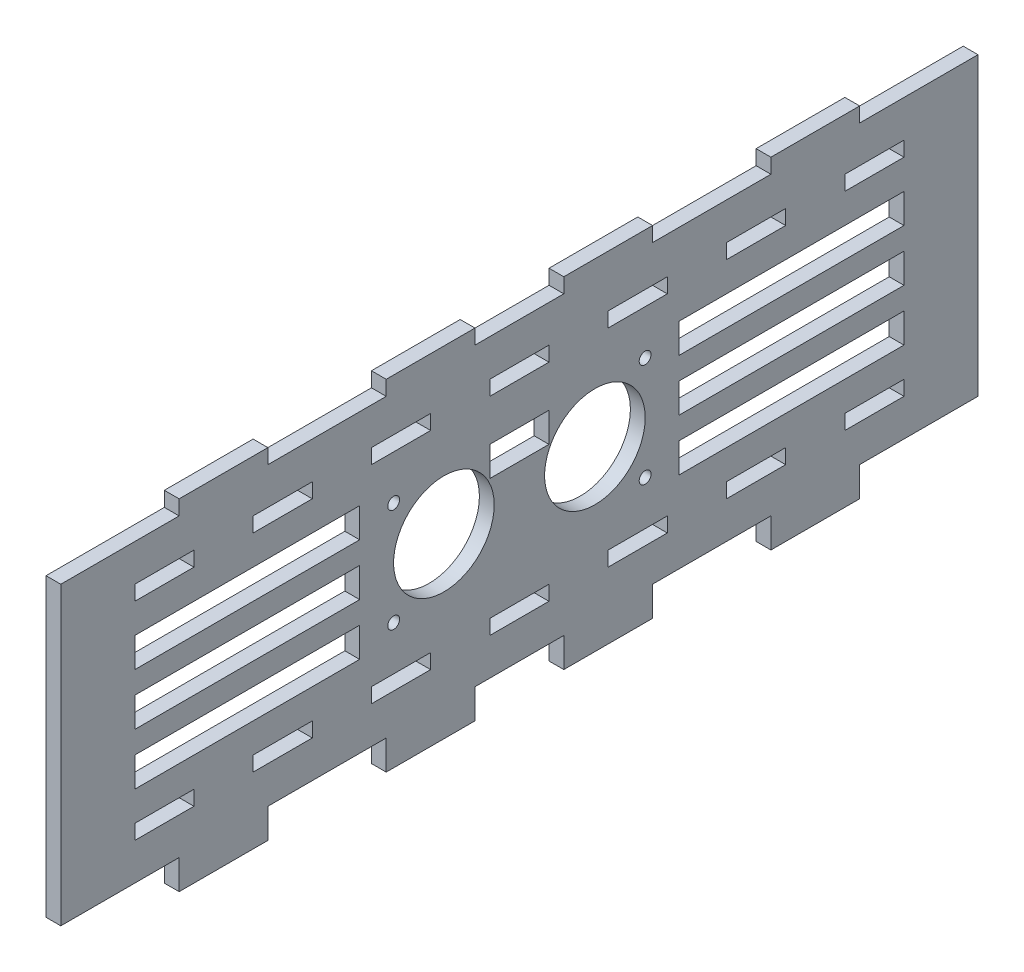
SolidWorks part; units mm, degrees
material "Maple"
ref_plane "Front Plane" through (0, 0, 0) normal (0, 0, 1) x (1, 0, 0)
ref_plane "Top Plane" through (0, 0, 0) normal (0, 1, 0) x (1, 0, 0)
ref_plane "Right Plane" through (0, 0, 0) normal (1, 0, 0) x (0, 0, -1)
sketch "Sketch1" plane through (0, 0, 0) normal (1, 0, 0) x (0, 0, -1)
  line L0 (-77.507, 27.5) -> (77.507, 27.5) construction
  line L1 (-77.507, -25) -> (77.507, -25) construction
  line L2 (-77.507, -25) -> (-77.507, 25) construction
  line L3 (-77.507, 25) -> (77.507, 25) construction
  line L4 (77.507, -25) -> (77.507, 25) construction
  line L5 (-77.507, -25) -> (77.507, 25) construction
  line L6 (-77.507, 25) -> (77.507, -25) construction
  line L7 (-77.507, -30) -> (77.507, -30) construction
  line L8 (-20.5112, 0) -> (21.2154, 0) construction
  line L9 (0, 22.6869) -> (0, -9.8875) construction
  line L10 (-77.507, 25) -> (-77.507, -25)
  line L11 (-77.507, -25) -> (-57.507, -25)
  line L12 (-57.507, -25) -> (-57.507, -30)
  line L13 (-57.507, -30) -> (-42.507, -30)
  line L14 (-42.507, -30) -> (-42.507, -25)
  line L15 (-42.507, -25) -> (-22.507, -25)
  line L16 (-22.507, -25) -> (-22.507, -30)
  line L17 (-22.507, -30) -> (-7.507, -30)
  line L18 (-7.507, -30) -> (-7.507, -25)
  line L19 (-7.507, -25) -> (7.507, -25)
  line L20 (-7.507, 25) -> (7.507, 25)
  line L21 (-7.507, 27.5) -> (-7.507, 25)
  line L22 (-22.507, 27.5) -> (-7.507, 27.5)
  line L23 (-22.507, 25) -> (-22.507, 27.5)
  line L24 (-42.507, 25) -> (-22.507, 25)
  line L25 (-42.507, 27.5) -> (-42.507, 25)
  line L26 (-57.507, 27.5) -> (-42.507, 27.5)
  line L27 (-57.507, 25) -> (-57.507, 27.5)
  line L28 (-77.507, 25) -> (-57.507, 25)
  line L29 (7.507, -30) -> (7.507, -25)
  line L30 (22.507, -30) -> (7.507, -30)
  line L31 (22.507, -25) -> (22.507, -30)
  line L32 (42.507, -25) -> (22.507, -25)
  line L33 (42.507, -30) -> (42.507, -25)
  line L34 (57.507, -30) -> (42.507, -30)
  line L35 (57.507, -25) -> (57.507, -30)
  line L36 (77.507, -25) -> (57.507, -25)
  line L37 (77.507, 25) -> (77.507, -25)
  line L38 (77.507, 25) -> (57.507, 25)
  line L39 (57.507, 25) -> (57.507, 27.5)
  line L40 (57.507, 27.5) -> (42.507, 27.5)
  line L41 (42.507, 27.5) -> (42.507, 25)
  line L42 (42.507, 25) -> (22.507, 25)
  line L43 (22.507, 25) -> (22.507, 27.5)
  line L44 (22.507, 27.5) -> (7.507, 27.5)
  line L45 (7.507, 27.5) -> (7.507, 25)
  line L46 (-5, 16.25) -> (5, 16.25)
  line L51 (-65, -11.25) -> (-65, -6.25)
  line L52 (-27, -11.25) -> (-65, -11.25)
  line L57 (-27, -6.25) -> (-27, -11.25)
  line L58 (-65, -6.25) -> (-27, -6.25)
  line L59 (-5, -18.75) -> (5, -18.75)
  line L60 (-5, -18.75) -> (-5, -16.25)
  line L61 (-5, -16.25) -> (5, -16.25)
  line L62 (5, -18.75) -> (5, -16.25)
  line L63 (-5, -18.75) -> (5, -16.25) construction
  line L64 (-5, -16.25) -> (5, -18.75) construction
  line L65 (5, 18.75) -> (5, 16.25)
  line L66 (-5, 18.75) -> (5, 18.75)
  line L67 (-5, 18.75) -> (-5, 16.25)
  line L68 (-25, -18.75) -> (-25, -16.25)
  line L69 (-25, -18.75) -> (-15, -18.75)
  line L70 (-15, -18.75) -> (-15, -16.25)
  line L71 (-25, -16.25) -> (-15, -16.25)
  line L72 (-25, 16.25) -> (-15, 16.25)
  line L73 (-15, 18.75) -> (-15, 16.25)
  line L74 (-25, 18.75) -> (-15, 18.75)
  line L75 (-25, 18.75) -> (-25, 16.25)
  line L76 (-45, -18.75) -> (-45, -16.25)
  line L77 (-45, -18.75) -> (-35, -18.75)
  line L78 (-35, -18.75) -> (-35, -16.25)
  line L79 (-45, -16.25) -> (-35, -16.25)
  line L80 (-45, 16.25) -> (-35, 16.25)
  line L81 (-35, 18.75) -> (-35, 16.25)
  line L82 (-45, 18.75) -> (-35, 18.75)
  line L83 (-45, 18.75) -> (-45, 16.25)
  line L84 (-65, -18.75) -> (-65, -16.25)
  line L85 (-65, -18.75) -> (-55, -18.75)
  line L86 (-55, -18.75) -> (-55, -16.25)
  line L87 (-65, -16.25) -> (-55, -16.25)
  line L88 (-65, 16.25) -> (-55, 16.25)
  line L89 (-55, 18.75) -> (-55, 16.25)
  line L90 (-65, 18.75) -> (-55, 18.75)
  line L91 (-65, 18.75) -> (-65, 16.25)
  line L92 (15, -18.75) -> (15, -16.25)
  line L93 (15, -18.75) -> (25, -18.75)
  line L94 (25, -18.75) -> (25, -16.25)
  line L95 (15, -16.25) -> (25, -16.25)
  line L96 (15, 16.25) -> (25, 16.25)
  line L97 (25, 18.75) -> (25, 16.25)
  line L98 (15, 18.75) -> (25, 18.75)
  line L99 (15, 18.75) -> (15, 16.25)
  line L100 (35, -18.75) -> (35, -16.25)
  line L101 (35, -18.75) -> (45, -18.75)
  line L102 (45, -18.75) -> (45, -16.25)
  line L103 (35, -16.25) -> (45, -16.25)
  line L104 (35, 16.25) -> (45, 16.25)
  line L105 (45, 18.75) -> (45, 16.25)
  line L106 (35, 18.75) -> (45, 18.75)
  line L107 (35, 18.75) -> (35, 16.25)
  line L108 (55, -18.75) -> (55, -16.25)
  line L109 (55, -18.75) -> (65, -18.75)
  line L110 (65, -18.75) -> (65, -16.25)
  line L111 (55, -16.25) -> (65, -16.25)
  line L112 (55, 16.25) -> (65, 16.25)
  line L113 (65, 18.75) -> (65, 16.25)
  line L114 (55, 18.75) -> (65, 18.75)
  line L115 (55, 18.75) -> (55, 16.25)
  line L120 (65, 11.25) -> (27, 11.25)
  line L121 (27, 11.25) -> (27, 6.25)
  line L122 (27, 6.25) -> (65, 6.25)
  line L123 (65, 6.25) -> (65, 11.25)
  line L124 (65, 11.25) -> (27, 11.25)
  line L125 (27, 11.25) -> (27, 6.25)
  line L126 (27, 6.25) -> (65, 6.25)
  line L127 (65, 6.25) -> (65, 11.25)
  line L128 (0, -6.5734) -> (0, 15.6465) construction
  line L147 (-13.9777, 0) -> (-4.3511, 0) construction
  line L152 (-65, -2.5) -> (-27, -2.5)
  line L153 (-27, -2.5) -> (-27, 2.5)
  line L154 (-27, 2.5) -> (-65, 2.5)
  line L155 (-65, 2.5) -> (-65, -2.5)
  line L156 (-65, -2.5) -> (-27, -2.5)
  line L157 (-27, -2.5) -> (-27, 2.5)
  line L158 (-27, 2.5) -> (-65, 2.5)
  line L159 (-65, 2.5) -> (-65, -2.5)
  line L160 (-27, 11.25) -> (-65, 11.25)
  line L161 (-65, 11.25) -> (-65, 6.25)
  line L162 (-65, 6.25) -> (-27, 6.25)
  line L163 (-27, 6.25) -> (-27, 11.25)
  line L164 (-27, 11.25) -> (-65, 11.25)
  line L165 (-65, 11.25) -> (-65, 6.25)
  line L166 (-65, 6.25) -> (-27, 6.25)
  line L167 (-27, 6.25) -> (-27, 11.25)
  line L168 (65, -6.25) -> (27, -6.25)
  line L169 (27, -6.25) -> (27, -11.25)
  line L170 (27, -11.25) -> (65, -11.25)
  line L171 (65, -11.25) -> (65, -6.25)
  line L172 (65, -6.25) -> (27, -6.25)
  line L173 (27, -6.25) -> (27, -11.25)
  line L174 (27, -11.25) -> (65, -11.25)
  line L175 (65, -11.25) -> (65, -6.25)
  line L186 (-5, 4.22) -> (5, 4.22)
  line L187 (-5, 4.22) -> (-5, 9.22)
  line L192 (-5, 9.22) -> (5, 9.22)
  line L193 (5, 4.22) -> (5, 9.22)
  line L194 (-5, 4.22) -> (5, 9.22) construction
  line L195 (-5, 9.22) -> (5, 4.22) construction
  line L200 (65, 2.5) -> (27, 2.5)
  line L201 (27, 2.5) -> (27, -2.5)
  line L202 (27, -2.5) -> (65, -2.5)
  line L203 (65, -2.5) -> (65, 2.5)
  line L204 (65, 2.5) -> (27, 2.5)
  line L205 (27, 2.5) -> (27, -2.5)
  line L206 (27, -2.5) -> (65, -2.5)
  line L207 (65, -2.5) -> (65, 2.5)
  circle A2 centre (-21.25, 8.75) radius 1
  circle A3 centre (-12.76, 0) radius 8.5
  circle A6 centre (-21.25, -8.75) radius 1
  circle A7 centre (12.76, 0) radius 8.5
  circle A8 centre (21.25, -8.75) radius 1
  circle A9 centre (21.25, 8.75) radius 1
  point P0 (0, 0)
  point P11 (0, 22.6869)
  point P25 (0, 0)
  point P33 (-77.507, 0)
  point P34 (0, -25)
  point P49 (0, 25)
  point P54 (12.76, 0)
  point P55 (0, 0)
  point P56 (0, 0)
  point P57 (-21.26, 13.0072)
  point P58 (0, 0)
  point P59 (0, 0)
  point P60 (0, 0)
  point P61 (-21.25, -5.6837)
  point P62 (0, 0)
  point P66 (0, 0)
  point P68 (0, 0)
  point P71 (0, -17.5)
  point P140 (0, 0)
  point P141 (0, 0)
  point P143 (0, 0)
  point P145 (0, 0)
  point P156 (0, 6.72)
  dimension "D7" = 6.72
  dimension "D9" = 17
  dimension "D10" = 42.5
  dimension "D11" = 2
  dimension "D3" = 155.014
  dimension "D4" = 50
  dimension "D5" = 15
  dimension "D6" = 20
  dimension "D8" = 17.5
  dimension "D12" = 12.76
  dimension "D15" = 10
  dimension "D16" = 10
  dimension "D2" = 5
  dimension "D17" = 17.5
  dimension "D18" = 2.5
  dimension "D21" = 10
  dimension "D22" = 10
  dimension "D24" = 5
  dimension "D1" = 2.5
  dimension "D23" = 0
  dimension "D27" = 0
  dimension "D28" = 0
  dimension "D29" = 0
  dimension "D33" = 0
  dimension "D19" = 4
  dimension "D20" = 4
extrude "Boss-Extrude1" add sketch "Sketch1" along normal mid plane 2.5
